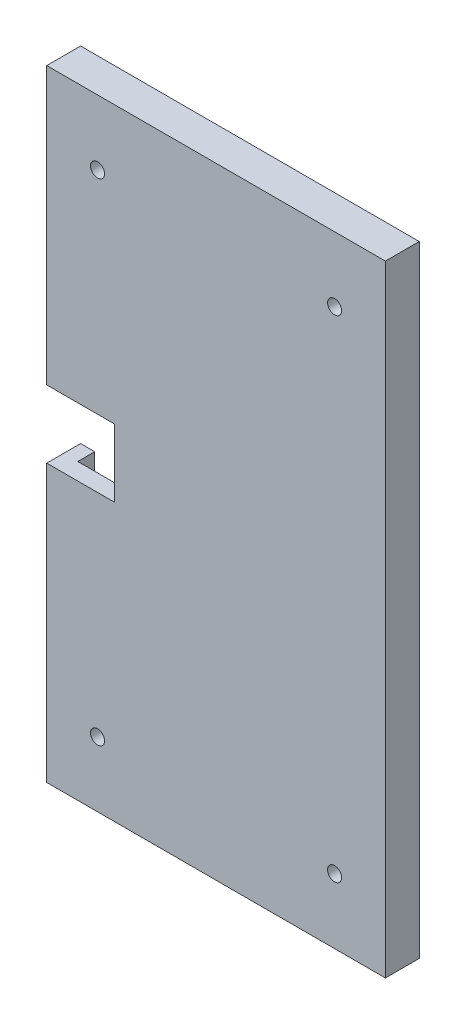
SolidWorks part; units mm, degrees
ref_plane "前视基准面" through (0, 0, 0) normal (0, 0, 1) x (1, 0, 0)
ref_plane "上视基准面" through (0, 0, 0) normal (0, 1, 0) x (1, 0, 0)
ref_plane "右视基准面" through (0, 0, 0) normal (1, 0, 0) x (0, 0, -1)
sketch "草图1" plane through (0, 0, 0) normal (0, 0, 1) x (1, 0, 0)
  line L13 (-25, 50) -> (25, 50)
  line L14 (-25, 50) -> (-25, -50)
  line L15 (-25, -50) -> (25, -50)
  line L16 (25, 50) -> (25, -50)
  line L17 (-30, 55) -> (30, 55)
  line L18 (-30, 55) -> (-30, -55)
  line L19 (-30, -55) -> (30, -55)
  line L20 (30, 55) -> (30, -55)
  circle A0 centre (-21, 43.5) radius 1.25
  circle A1 centre (21, 43.5) radius 1.25
  circle A2 centre (-21, -43.5) radius 1.25
  circle A3 centre (21, -43.5) radius 1.25
  dimension "D12" = 4
  dimension "D14" = 6.5
  dimension "D15" = 6.5
  dimension "D16" = 4
  dimension "D17" = 2.5
  dimension "D18" = 2.5
  dimension "D19" = 2.5
  dimension "D20" = 2.5
  dimension "D1" = 100
  dimension "D2" = 50
  dimension "D3" = 25
  dimension "D4" = 50
  dimension "D5" = 5
  dimension "D6" = 5
  dimension "D7" = 5
  dimension "D8" = 5
  dimension "D9" = 4
  dimension "D10" = 6.5
  dimension "D11" = 6.5
  dimension "D13" = 4
extrude "凸台-拉伸1" add sketch "草图1" along normal blind 6 contours L16 L13 L14 L15 A3 A2 A1 A0 | L20 L17 L18 L19 L13 L16 L15 L14
sketch "草图2" plane through (0, 0, 0) normal (0, 0, -1) x (-1, 0, 0)
sketch "草图3" plane through (0, 0, 0) normal (0, 0, -1) x (-1, 0, 0)
  line L0 (25, 6) -> (30, 6)
  line L1 (-25, 50) -> (25, 50)
  line L2 (-25, 50) -> (-25, -50)
  line L3 (-25, -50) -> (25, -50)
  line L4 (25, 50) -> (25, -50)
  line L5 (30, 55) -> (30, -55) construction
  line L6 (30, 6) -> (30, -6)
  line L7 (30, -6) -> (25, -6)
  line L8 (25, -6) -> (25, 6)
  circle M5 centre (-21, -43.5) radius 1.25
  circle M6 centre (21, -43.5) radius 1.25
  circle M7 centre (-21, 43.5) radius 1.25
  circle M8 centre (21, 43.5) radius 1.25
  line M11 (30, -55) -> (30, 55)
  dimension "D1" = 50
  dimension "D2" = 100
  dimension "D3" = 25
  dimension "D4" = 50
  dimension "D5" = 44
  dimension "D6" = 44
extrude "切除-拉伸2" cut sketch "草图3" against normal blind 3 contours L7 L0 L4 M11 | L4 L1 L2 L3 M6 M8 M7 M5
sketch "草图4" plane through (0, 0, 3) normal (0, 0, -1) x (-1, 0, 0)
  line L0 (-25, 50) -> (25, 50) construction
  line L1 (-10, 44) -> (15, 44)
  line L2 (-10, 44) -> (-10, -44)
  line L3 (-10, -44) -> (15, -44)
  line L4 (15, 44) -> (15, -44)
  line L5 (-25, -50) -> (25, -50) construction
  line L6 (18, 6) -> (18, -6)
  line L7 (18, -6) -> (30, -6)
  line L8 (30, -6) -> (30, 6) construction
  line L9 (30, -6) -> (30, 6)
  line L10 (30, 6) -> (18, 6)
  line L11 (25, 50) -> (25, 6) construction
  point P6 (0, 50)
  dimension "D1" = 6
  dimension "D2" = 6
  dimension "D3" = 25
  dimension "D4" = 12
  dimension "D5" = 10
extrude "切除-拉伸3" cut sketch "草图4" against normal blind 2 contours L4 L1 L2 L3
sketch "草图5" plane through (0, 0, 3) normal (0, 0, -1) x (-1, 0, 0)
  line L0 (18, 6) -> (18, -6)
  line L1 (18, -6) -> (30, -6)
  line L2 (30, -6) -> (30, -55) construction
  line L3 (30, -6) -> (30, 6)
  line L4 (30, -6) -> (30, 6) construction
  line L5 (30, 6) -> (18, 6)
  dimension "D1" = 12
extrude "切除-拉伸4" cut sketch "草图5" against normal through all
sketch "草图6" plane through (0, 0, 3) normal (0, 0, -1) x (-1, 0, 0)
  line L1 (-27.5, 50) -> (-27.5, -50)
  line L2 (-27.5, -50) -> (27.5, -50)
  line L3 (27.5, -50) -> (27.5, 50)
  line L5 (-27.5, 50) -> (27.5, 50)
  line L6 (-30, 55) -> (-30, -55) construction
  dimension "D1" = 55
  dimension "D2" = 100
  dimension "D3" = 2.5
  dimension "D4" = 50
extrude "切除-拉伸5" cut sketch "草图6" along normal through all
